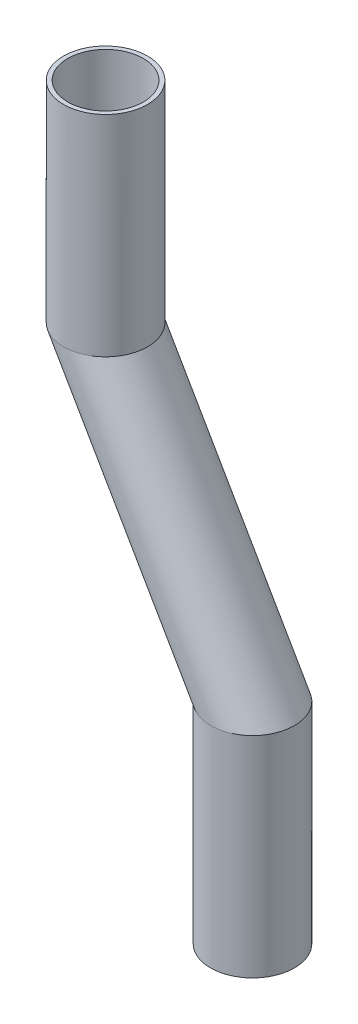
SolidWorks part; units mm, degrees
ref_plane "Front Plane" through (0, 0, 0) normal (0, 0, 1) x (1, 0, 0)
ref_plane "Top Plane" through (0, 0, 0) normal (0, 1, 0) x (1, 0, 0)
ref_plane "Right Plane" through (0, 0, 0) normal (1, 0, 0) x (0, 0, -1)
sketch "Sketch1" plane through (0, 0, 0) normal (0, 1, 0) x (1, 0, 0)
  circle A0 centre (0, 0) radius 10
  circle A1 centre (0, 0) radius 9
  dimension "D1" = 20
  dimension "D2" = 18
extrude "Boss-Extrude1" add sketch "Sketch1" along normal blind 50
sketch "Sketch2" plane through (0, 0, 0) normal (0, -1, 0) x (1, 0, 0)
  circle A0 centre (0, 0) radius 9
  circle A1 centre (0, 0) radius 10
  dimension "D1" = 18
  dimension "D2" = 20
sketch "Sketch3" plane through (0, 0, 0) normal (0, 0, 1) x (1, 0, 0)
  line L0 (0, 0) -> (35, -60.6218)
  line L1 (0, 0) -> (0, -62.8745) construction
  dimension "D1" = 70
  dimension "D2" = 30
sweep "Sweep1" add profiles "Sketch2" path "Sketch3"
sketch "Sketch4" plane through (0, -60.6218, 0) normal (0, -1, 0) x (1, 0, 0)
  line L0 (0, 0) -> (35, 0) construction
  circle A0 centre (35, 0) radius 9
  circle A1 centre (35, 0) radius 10
  dimension "D1" = 20
  dimension "D2" = 18
  dimension "D3" = 35
sketch "Sketch5" plane through (0, 0, 0) normal (0, 0, 1) x (1, 0, 0)
  line L0 (35, -60.6218) -> (35, -110.6218)
  line L1 (25, -60.6218) -> (45, -60.6218) construction
  dimension "D1" = 50
sweep "Sweep2" add profiles "Sketch4" path "Sketch5"
